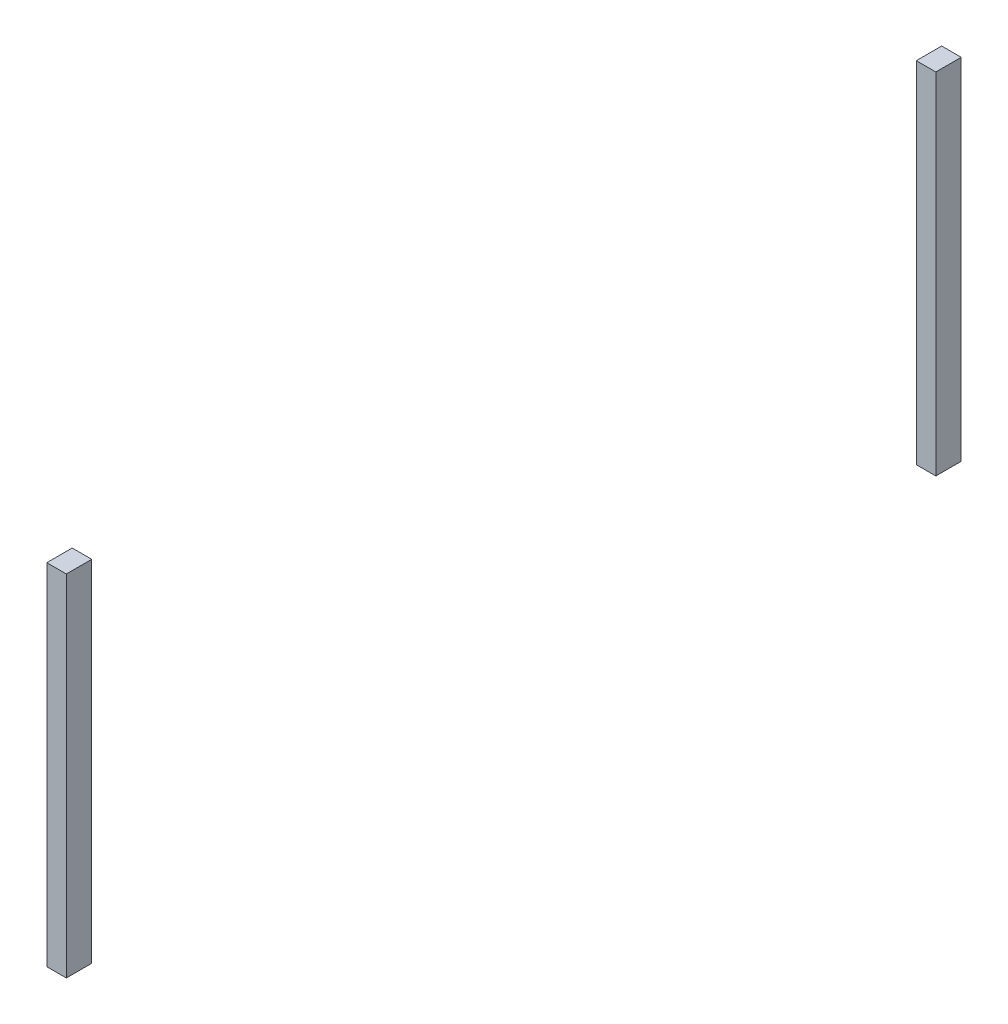
SolidWorks part; units mm, degrees
ref_plane "Front Plane" through (0, 0, 0) normal (0, 0, 1) x (1, 0, 0)
ref_plane "Top Plane" through (0, 0, 0) normal (0, 1, 0) x (1, 0, 0)
ref_plane "Right Plane" through (0, 0, 0) normal (1, 0, 0) x (0, 0, -1)
ref_plane "Plane2" through (-256.75, 0, 0) normal (1, 0, 0) x (0, 0, -1)
sketch "Sketch5" plane through (-256.75, 0, 0) normal (1, 0, 0) x (0, 0, -1)
  line L0 (-1970.8, 151) -> (-1970.8, -400)
  line L1 (-1970.8, -400) -> (-1930.8, -400)
  line L2 (-1930.8, -400) -> (-1930.8, 151)
  line L3 (-1930.8, 151) -> (-1970.8, 151)
  dimension "D1" = 40
  dimension "D2" = 551
extrude "Boss-Extrude2" add sketch "Sketch5" against normal blind 30.8 separate body
sketch "Sketch10" plane through (-256.75, 0, 0) normal (1, 0, 0) x (0, 0, -1)
  line L0 (-601.6, 151) -> (-601.6, -400)
  line L1 (-601.6, -400) -> (-561.6, -400)
  line L2 (-561.6, -400) -> (-561.6, 151)
  line L3 (-561.6, 151) -> (-601.6, 151)
  line L4 (-1970.8, 151) -> (-1970.8, -400) construction
  dimension "D1" = 40
  dimension "D2" = 1409.2
  dimension "D3" = 551
extrude "Boss-Extrude3" add sketch "Sketch10" against normal blind 30.8 separate body
